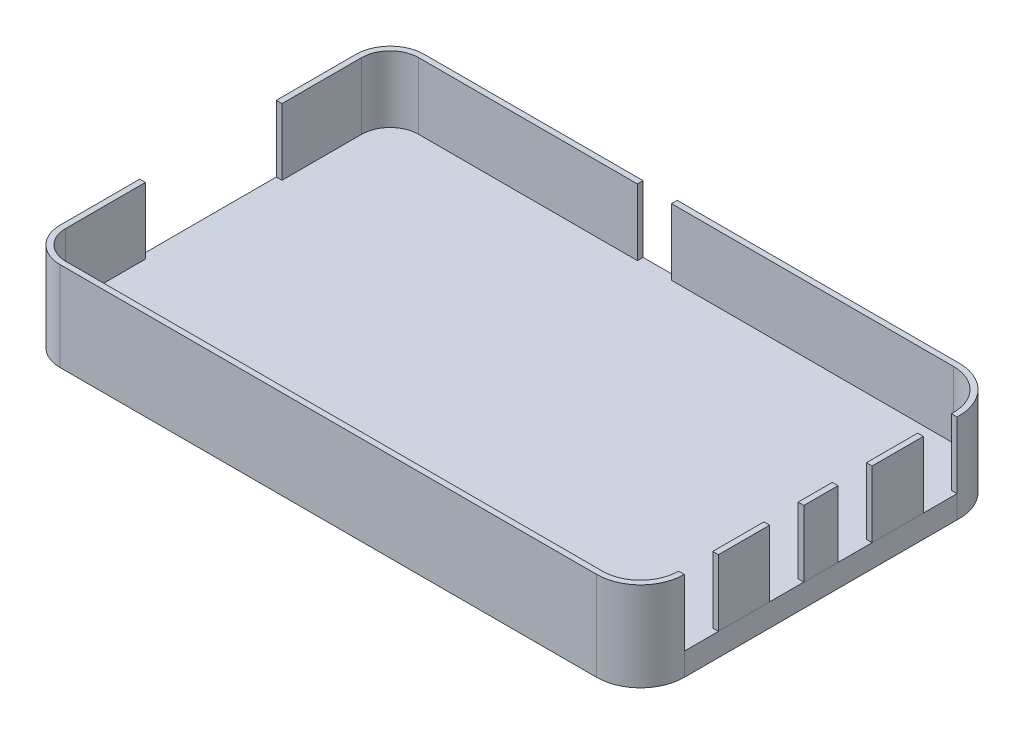
SolidWorks part; units mm, degrees
ref_plane "Front" through (0, 0, 0) normal (0, 0, 1) x (1, 0, 0)
ref_plane "Top" through (0, 0, 0) normal (0, 1, 0) x (1, 0, 0)
ref_plane "Right" through (0, 0, 0) normal (1, 0, 0) x (0, 0, -1)
sketch "Çizim5" plane through (0, 0, 0) normal (0, 1, 0) x (1, 0, 0)
  line L0 (49.9989, 33.5465) -> (25.225, 33.5465)
  line L5 (49.9989, 34.0465) -> (25.225, 34.0465)
  line L6 (50.1491, 2.0465) -> (3.0007, 2.0465)
  line L7 (0, 5.0472) -> (0, 12.0465)
  line L8 (0, 24.0465) -> (0, 31.0457)
  line L9 (22.225, 34.0465) -> (3.0007, 34.0465)
  line L10 (50.1491, 2.5465) -> (3.0007, 2.5465)
  line L11 (0.5, 5.0472) -> (0.5, 12.0465)
  line L12 (0.5, 24.0465) -> (0.5, 31.0457)
  line L13 (22.225, 33.5465) -> (3.0007, 33.5465)
  line L14 (53.5, 26.8965) -> (53.5, 22.3965)
  line L15 (53.5, 19.3965) -> (53.5, 16.3965)
  line L16 (53.5, 13.3965) -> (53.5, 8.8965)
  line L17 (54, 26.8965) -> (54, 22.3965)
  line L18 (54, 19.3965) -> (54, 16.3965)
  line L19 (54, 13.3965) -> (54, 8.8965)
  line L20 (0, 12.0465) -> (0.5, 12.0465)
  line L21 (0, 24.0465) -> (0.5, 24.0465)
  line L22 (22.225, 34.0465) -> (22.225, 33.5465)
  line L23 (25.225, 34.0465) -> (25.225, 33.5465)
  line L24 (53.4994, 29.8723) -> (53.9988, 29.8481)
  line L25 (54, 26.8965) -> (53.5, 26.8965)
  line L26 (54, 22.3965) -> (53.5, 22.3965)
  line L27 (54, 19.3965) -> (53.5, 19.3965)
  line L28 (54, 16.3965) -> (53.5, 16.3965)
  line L29 (54, 13.3965) -> (53.5, 13.3965)
  line L30 (54, 8.8965) -> (53.5, 8.8965)
  line L31 (54, 5.8962) -> (53.5, 5.8963)
  arc A0 (49.9989, 33.5465) -> (53.4994, 29.8723) centre (49.9989, 30.0418) cw
  arc A1 (50.1491, 2.5465) -> (53.5, 5.8963) centre (50.1491, 5.8973) ccw
  arc A2 (0.5, 5.0472) -> (3.0007, 2.5465) centre (3.0007, 5.0472) ccw
  arc A3 (50.1491, 2.0465) -> (54, 5.8962) centre (50.1491, 5.8973) ccw
  arc A4 (0, 5.0472) -> (3.0007, 2.0465) centre (3.0007, 5.0472) ccw
  arc A5 (0, 31.0457) -> (3.0007, 34.0465) centre (3.0007, 31.0457) cw
  arc A6 (49.9989, 34.0465) -> (53.9988, 29.8481) centre (49.9989, 30.0418) cw
  arc A7 (0.5, 31.0457) -> (3.0007, 33.5465) centre (3.0007, 31.0457) cw
  dimension "D1" = 0.5
  dimension "D2" = 0.5
extrude "Yükseklik-Ekstrüzyon6" add sketch "Çizim5" along normal up to vertex (5.8369 mm away)
sketch "Çizim6" plane through (0, 0, 0) normal (0, -1, 0) x (1, 0, 0)
  line L0 (0, -31.0457) -> (0, -5.0472)
  line L1 (3.0007, -2.0465) -> (50.1491, -2.0465)
  line L2 (54, -5.8962) -> (53.9988, -29.8481)
  line L3 (49.9989, -34.0465) -> (3.0007, -34.0465)
  arc A0 (49.9989, -34.0465) -> (53.9988, -29.8481) centre (49.9989, -30.0418) ccw
  arc A1 (54, -5.8962) -> (50.1491, -2.0465) centre (50.1491, -5.8973) ccw
  arc A2 (3.0007, -2.0465) -> (0, -5.0472) centre (3.0007, -5.0472) ccw
  arc A3 (3.0007, -34.0465) -> (0, -31.0457) centre (3.0007, -31.0457) cw
extrude "Yükseklik-Ekstrüzyon7" add sketch "Çizim6" along normal blind 2
sketch "Çizim9" plane through (0, 0, 0) normal (0, 1, 0) x (1, 0, 0)
  circle A1 centre (3, 5.0465) radius 1.5
  circle A2 centre (50.5, 27.9465) radius 1
  circle A3 centre (50.5, 27.9465) radius 1.5
  circle A4 centre (3, 5.0465) radius 1
extrude "Yükseklik-Ekstrüzyon10" add sketch "Çizim9" along normal blind 1
sketch "Çizim15" plane through (0, -2, 0) normal (0, -1, 0) x (1, 0, 0)
  circle A0 centre (3, -5.0465) radius 1.5
  circle A1 centre (3, -5.0465) radius 1
  circle A2 centre (50.5, -27.9465) radius 1.5
  circle A3 centre (50.5, -27.9465) radius 1
extrude "Kes-Ekstrüzyon1" cut sketch "Çizim15" against normal blind 1
sketch "Çizim16" plane through (0, -2, 0) normal (0, -1, 0) x (1, 0, 0)
  circle A0 centre (3, -5.0465) radius 1
  circle A1 centre (50.5, -27.9465) radius 1
extrude "Kes-Ekstrüzyon2" cut sketch "Çizim16" against normal blind 9
